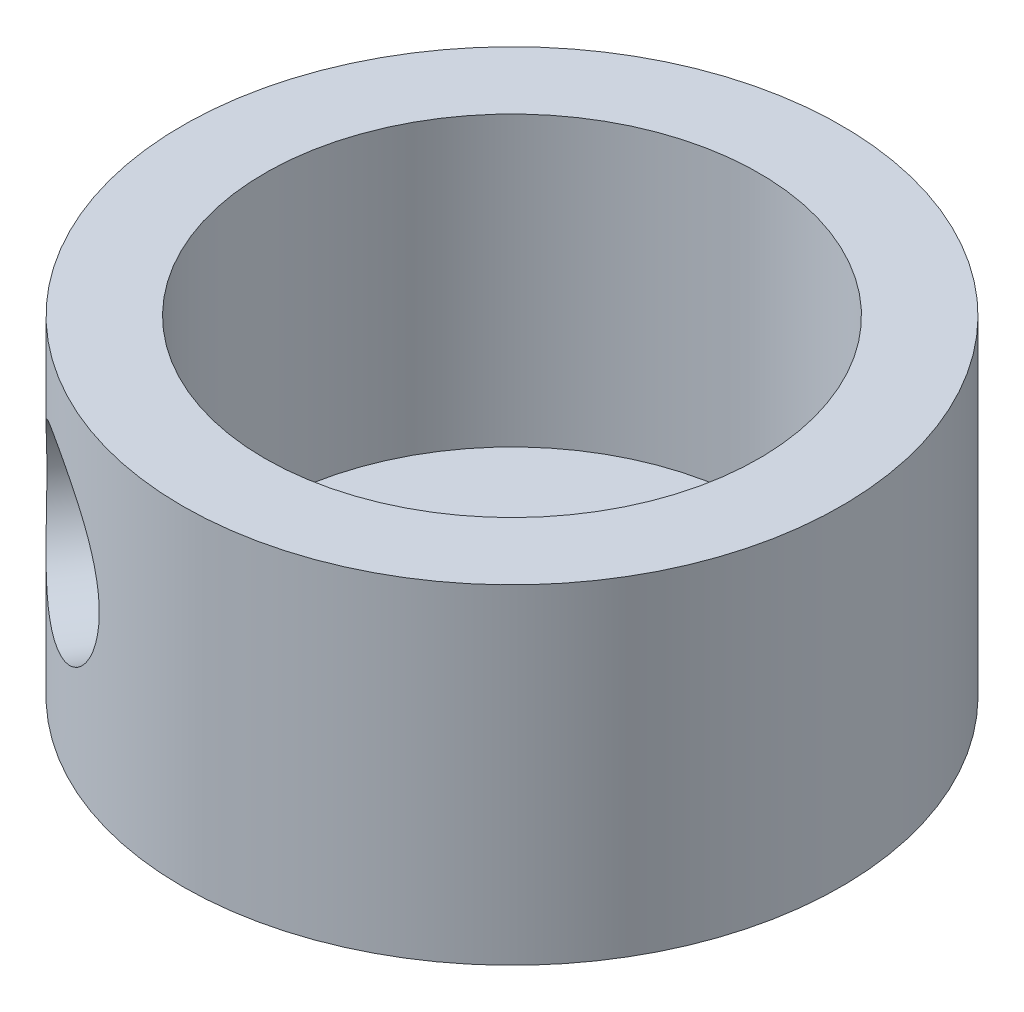
SolidWorks part; units mm, degrees
ref_plane "前基準面" through (0, 0, 0) normal (0, 0, 1) x (1, 0, 0)
ref_plane "上基準面" through (0, 0, 0) normal (0, 1, 0) x (1, 0, 0)
ref_plane "右基準面" through (0, 0, 0) normal (1, 0, 0) x (0, 0, -1)
sketch "草圖1" plane through (0, 0, 0) normal (0, 1, 0) x (1, 0, 0)
  circle A0 centre (0, 0) radius 40
  dimension "D1" = 80
extrude "填料-伸長1" add sketch "草圖1" along normal blind 40
sketch "草圖3" plane through (0, 40, 0) normal (0, 1, 0) x (1, 0, 0)
  circle A0 centre (0, 0) radius 30
  circle A1 centre (0, 0) radius 40 construction
  dimension "D1" = 10
extrude "除料-伸長2" cut sketch "草圖3" against normal blind 35
hole_wizard "Ø21.5 (21.5) 直徑孔1" positions "3D草圖1" profile "草圖4" hole size "Ø21.5" standard "JIS"
sketch3d "3D草圖1"
  point P0 (-21.7448, 21.9418, 33.5733)
sketch "草圖4" plane through (-21.7448, 21.9418, 33.5733) normal (0, 1, 0) x (0.8393, 0, 0.5436)
  line L0 (0, 0) -> (0, 10)
  line L1 (0, 10) -> (10.75, 10)
  line L2 (10.75, 10) -> (10.75, 0)
  line L5 (10.75, 0) -> (0, 0)
  line L11 (0, -6.35) -> (0, 107.95) construction
  dimension "貫穿孔直徑" = 21.5
  dimension "貫穿孔深度" = 10
